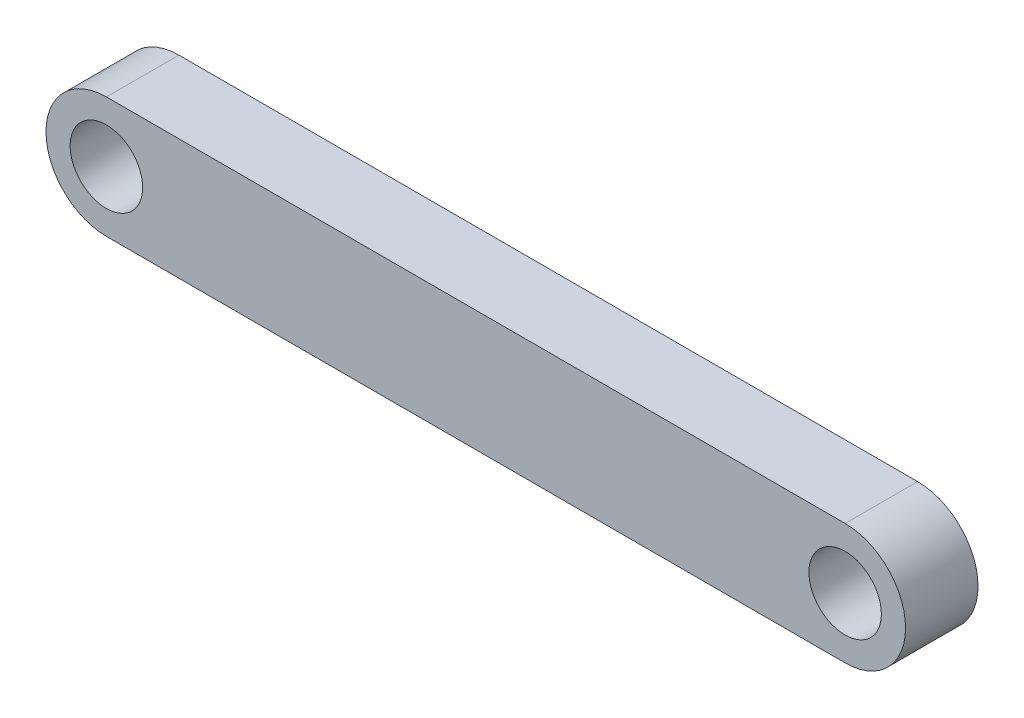
SolidWorks part; units mm, degrees
material "Plastique personnalisé"
ref_plane "Plan de face" through (0, 0, 0) normal (0, 0, 1) x (1, 0, 0)
ref_plane "Plan de dessus" through (0, 0, 0) normal (0, 1, 0) x (1, 0, 0)
ref_plane "Plan de droite" through (0, 0, 0) normal (1, 0, 0) x (0, 0, -1)
sketch "Esquisse1" plane through (0, 0, 0) normal (0, 0, 1) x (1, 0, 0)
  line L0 (0, 0) -> (30.58, 0) construction
  line L1 (0, 2.5) -> (30.58, 2.5)
  line L2 (0, -2.5) -> (30.58, -2.5)
  arc A0 (0, 2.5) -> (0, -2.5) centre (0, 0) ccw
  arc A1 (30.58, -2.5) -> (30.58, 2.5) centre (30.58, 0) ccw
  circle A2 centre (0, 0) radius 1.5
  circle A3 centre (30.58, 0) radius 1.5
  point P3 (15.29, 0)
  dimension "D2" = 5
  dimension "D3" = 3
  dimension "D4" = 3
  dimension "D1" = 30.58
extrude "Boss.-Extru.1" add sketch "Esquisse1" along normal blind 3
